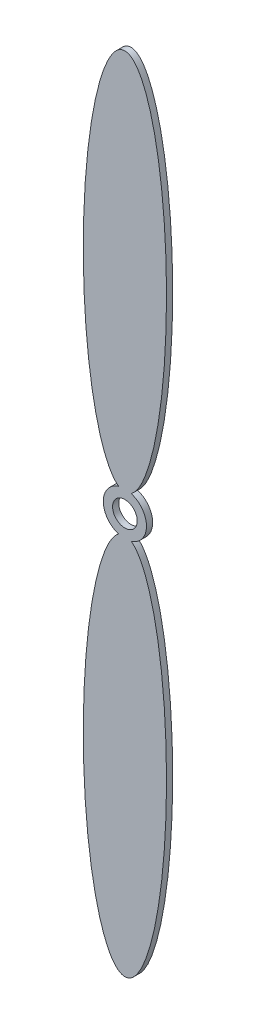
SolidWorks part; units mm, degrees
ref_plane "Front Plane" through (0, 0, 0) normal (0, 0, 1) x (1, 0, 0)
ref_plane "Top Plane" through (0, 0, 0) normal (0, 1, 0) x (1, 0, 0)
ref_plane "Right Plane" through (0, 0, 0) normal (1, 0, 0) x (0, 0, -1)
sketch "Sketch1" plane through (0, 0, 0) normal (0, 0, 1) x (1, 0, 0)
  circle A0 centre (0, 0) radius 130
  circle A1 centre (0, 0) radius 4
  circle A2 centre (0, 0) radius 7
  ellipse E0 centre (0, 68) end of major axis (0, 130) minor radius 13.5
  ellipse E1 centre (0, -68) end of major axis (0, -130) minor radius 13.5
extrude "Boss-Extrude3" add sketch "Sketch1" along normal blind 2 contours E1 A2 | E0 A2 | A2 E1 E0 A1 | E1 A2 | A2 E0
